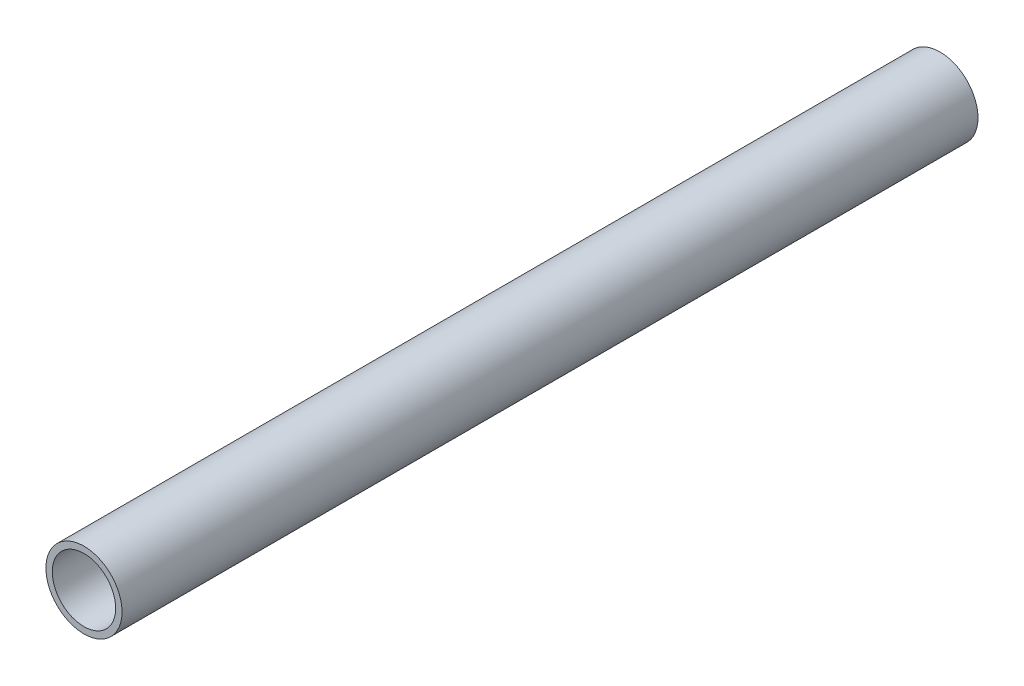
SolidWorks part; units mm, degrees
material "Zoltek Panex 33"
ref_plane "Front Plane" through (0, 0, 0) normal (0, 0, 1) x (1, 0, 0)
ref_plane "Top Plane" through (0, 0, 0) normal (0, 1, 0) x (1, 0, 0)
ref_plane "Right Plane" through (0, 0, 0) normal (1, 0, 0) x (0, 0, -1)
sketch "Sketch1" plane through (0, 0, 0) normal (0, 0, 1) x (1, 0, 0)
  circle A0 centre (0, 0) radius 6
  dimension "D1" = 12
extrude "Extrude-Thin1" add sketch "Sketch1" along normal blind 135 thin contours A0 thin type one direction reverse wall 1
